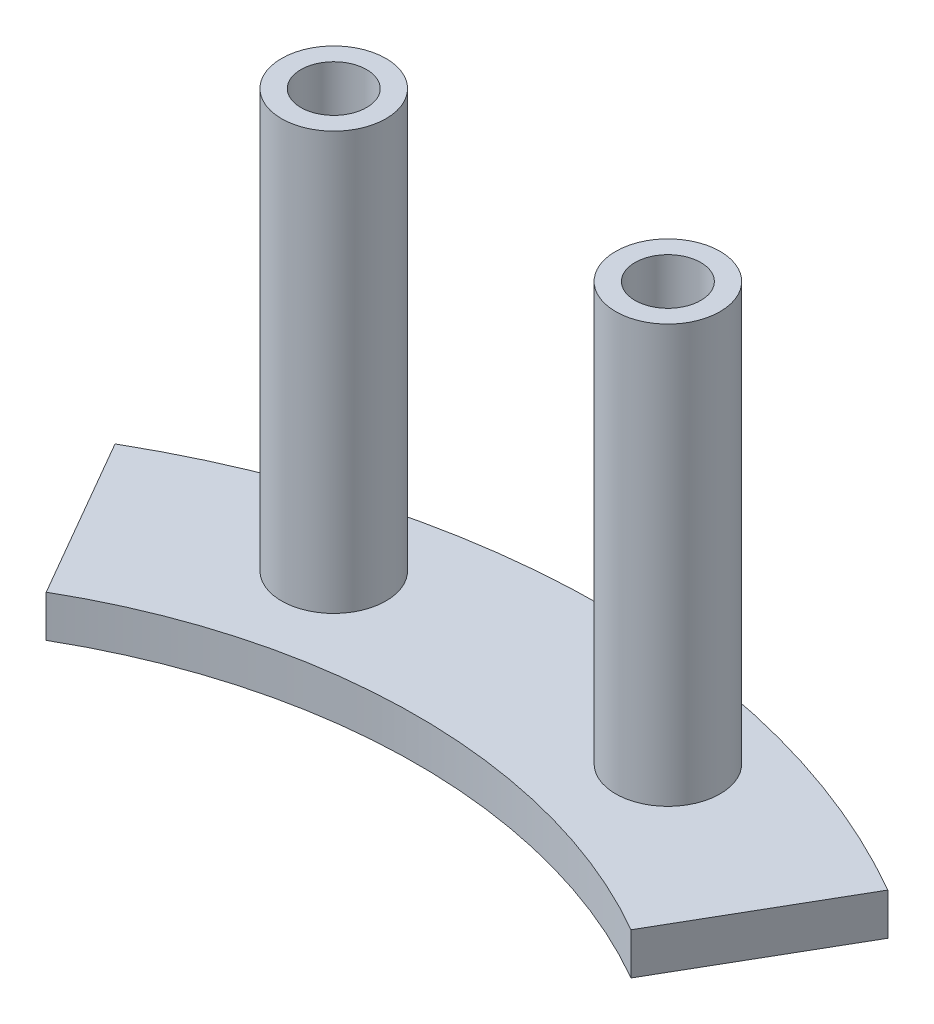
SolidWorks part; units mm, degrees
ref_plane "Front Plane" through (0, 0, 0) normal (0, 0, 1) x (1, 0, 0)
ref_plane "Top Plane" through (0, 0, 0) normal (0, 1, 0) x (1, 0, 0)
ref_plane "Right Plane" through (0, 0, 0) normal (1, 0, 0) x (0, 0, -1)
sketch "Sketch1" plane through (0, 0, 0) normal (0, 1, 0) x (1, 0, 0)
  line L0 (-14, 24.2487) -> (-18.5, 32.0429) construction
  line L1 (14, 24.2487) -> (18.5, 32.0429) construction
  line L2 (0, 0) -> (4, 0) construction
  line L3 (-18.5, 32.0429) -> (-14, 24.2487)
  line L4 (18.5, 32.0429) -> (14, 24.2487)
  circle A0 centre (0, 0) radius 28 construction
  circle A1 centre (0, 0) radius 37 construction
  arc A2 (-18.5, 32.0429) -> (18.5, 32.0429) centre (0, 0) cw
  arc A3 (-14, 24.2487) -> (14, 24.2487) centre (0, 0) cw
  arc A4 (-16.25, 28.1458) -> (16.25, 28.1458) centre (0, 0) cw construction
  dimension "D1" = 28
  dimension "D2" = 37
  dimension "D6" = 60
  dimension "D3" = 60
extrude "Boss-Extrude1" add sketch "Sketch1" along normal blind 2
sketch "Sketch2" plane through (0, 2, 0) normal (0, 1, 0) x (1, 0, 0)
  line L1 (14, 24.2487) -> (18.5, 32.0429) construction
  line L2 (-8, 32.0156) -> (8, 32.0156) construction
  line L3 (0, 32.0156) -> (0, 0) construction
  line L5 (-18.5, 32.0429) -> (-14, 24.2487) construction
  arc A0 (-16.5, 28.5788) -> (16.5, 28.5788) centre (0, 0) cw construction
  circle A1 centre (-8, 32.0156) radius 2.5
  circle A2 centre (8, 32.0156) radius 2.5
  dimension "D1" = 5
  dimension "D4" = 33
  dimension "D2" = 8
  dimension "D3" = 32.0156
extrude "Boss-Extrude2" add sketch "Sketch2" along normal blind 20
sketch "Sketch5" plane through (0, 22, 0) normal (0, 1, 0) x (1, 0, 0)
  circle A0 centre (-8, 32.0156) radius 1.575
  circle A2 centre (8, 32.0156) radius 1.575
  dimension "D1" = 3.15
extrude "Cut-Extrude1" cut sketch "Sketch5" against normal blind 3.5
